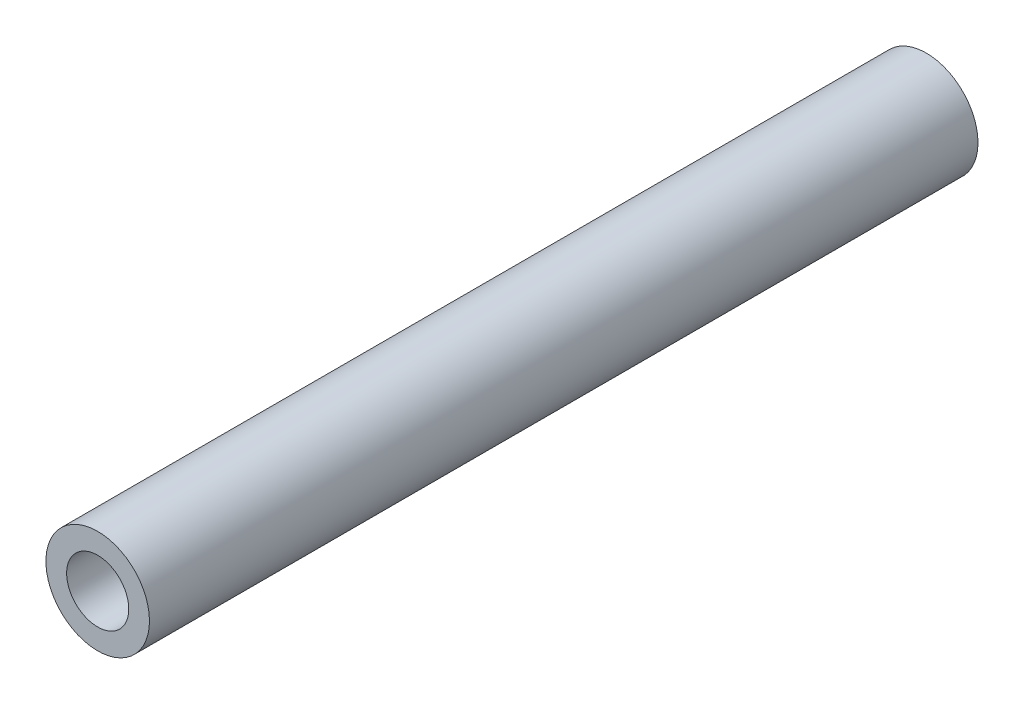
SolidWorks part; units mm, degrees
ref_plane "前视基准面" through (0, 0, 0) normal (0, 0, 1) x (1, 0, 0)
ref_plane "上视基准面" through (0, 0, 0) normal (0, 1, 0) x (1, 0, 0)
ref_plane "右视基准面" through (0, 0, 0) normal (1, 0, 0) x (0, 0, -1)
sketch "草图1" plane through (0, 0, 0) normal (0, 0, 1) x (1, 0, 0)
  circle A0 centre (0, 0) radius 1.5
  circle A2 centre (0, 0) radius 2.5
  dimension "D1" = 3
  dimension "D2" = 5
extrude "凸台-拉伸1" add sketch "草图1" along normal blind 40
